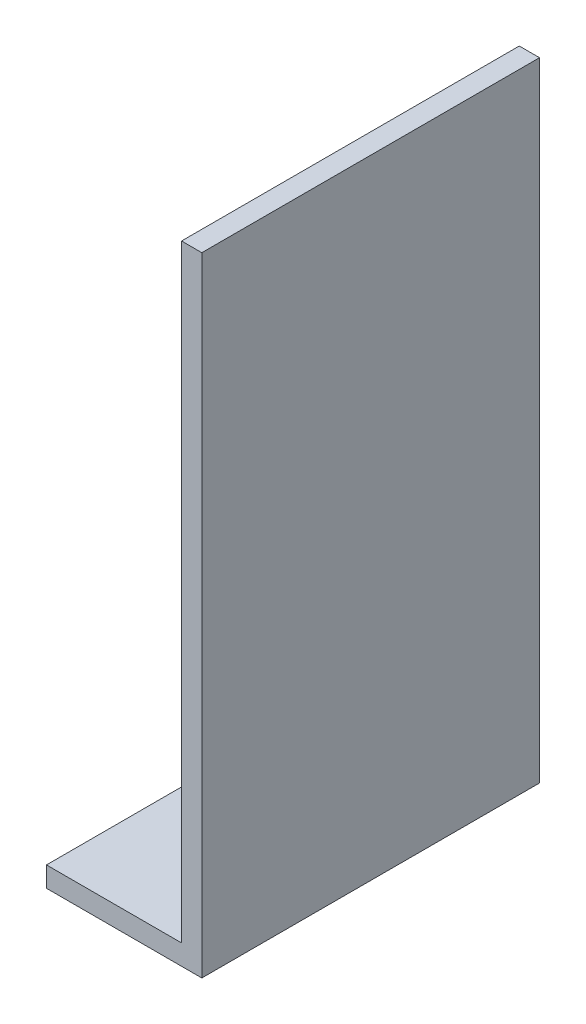
SolidWorks part; units mm, degrees
ref_plane "前视" through (0, 0, 0) normal (0, 0, 1) x (1, 0, 0)
ref_plane "上视" through (0, 0, 0) normal (0, 1, 0) x (1, 0, 0)
ref_plane "右视" through (0, 0, 0) normal (1, 0, 0) x (0, 0, -1)
sketch "Sketch1" plane through (0, 0, 0) normal (0, 1, 0) x (1, 0, 0)
  line L1 (0, 0) -> (23, 0)
  line L2 (0, 0) -> (0, 50)
  line L3 (0, 50) -> (23, 50)
  line L4 (23, 0) -> (23, 50)
  dimension "D1" = 50
  dimension "D2" = 23
extrude "Extrude1" add sketch "Sketch1" along normal blind 3
sketch "Sketch2" plane through (0, 3, 0) normal (0, 1, 0) x (1, 0, 0)
  line L0 (23, 50) -> (0, 50) construction
  line L1 (23, 0) -> (20, 0)
  line L2 (23, 0) -> (23, 50)
  line L3 (23, 50) -> (20, 50)
  line L4 (20, 0) -> (20, 50)
  dimension "D1" = 3
extrude "Extrude2" add sketch "Sketch2" along normal blind 90
